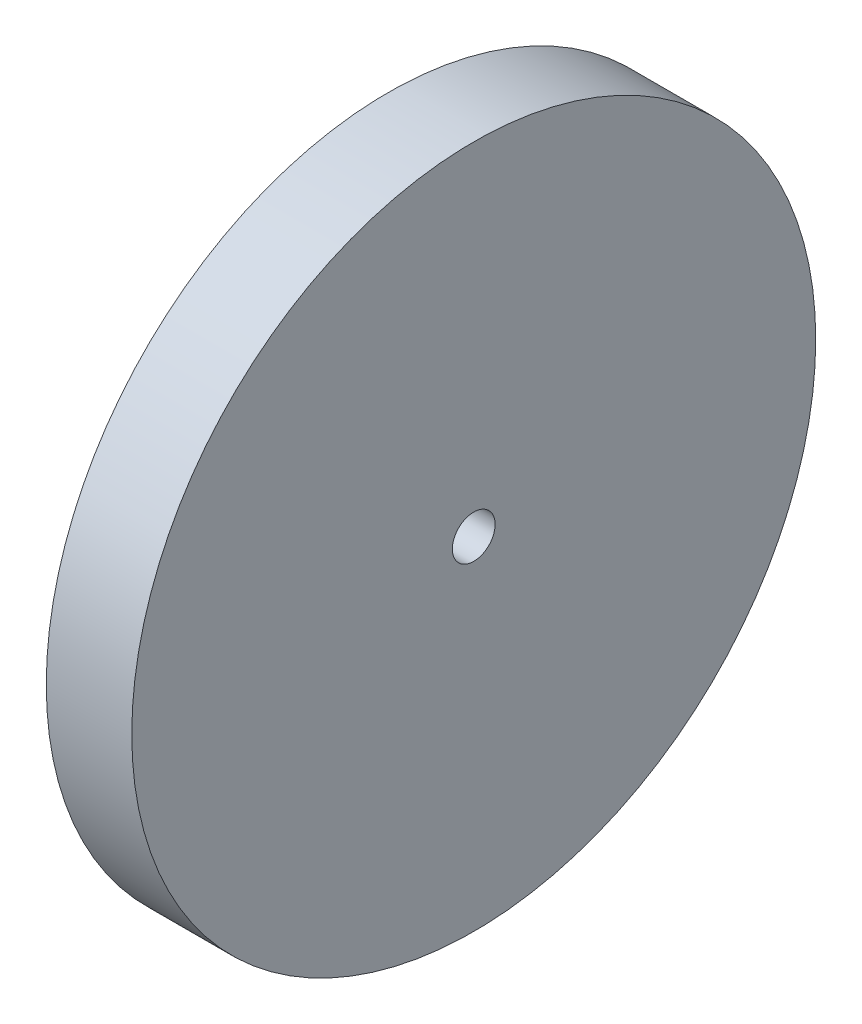
SolidWorks part; units mm, degrees
ref_plane "Front Plane" through (0, 0, 0) normal (0, 0, 1) x (1, 0, 0)
ref_plane "Top Plane" through (0, 0, 0) normal (0, 1, 0) x (1, 0, 0)
ref_plane "Right Plane" through (0, 0, 0) normal (1, 0, 0) x (0, 0, -1)
sketch "Sketch1" plane through (0, 0, 0) normal (1, 0, 0) x (0, 0, -1)
  circle A0 centre (0, 0) radius 80
  circle A1 centre (0, 0) radius 5
  dimension "D1" = 160
  dimension "D2" = 10
extrude "Boss-Extrude1" add sketch "Sketch1" along normal blind 20
